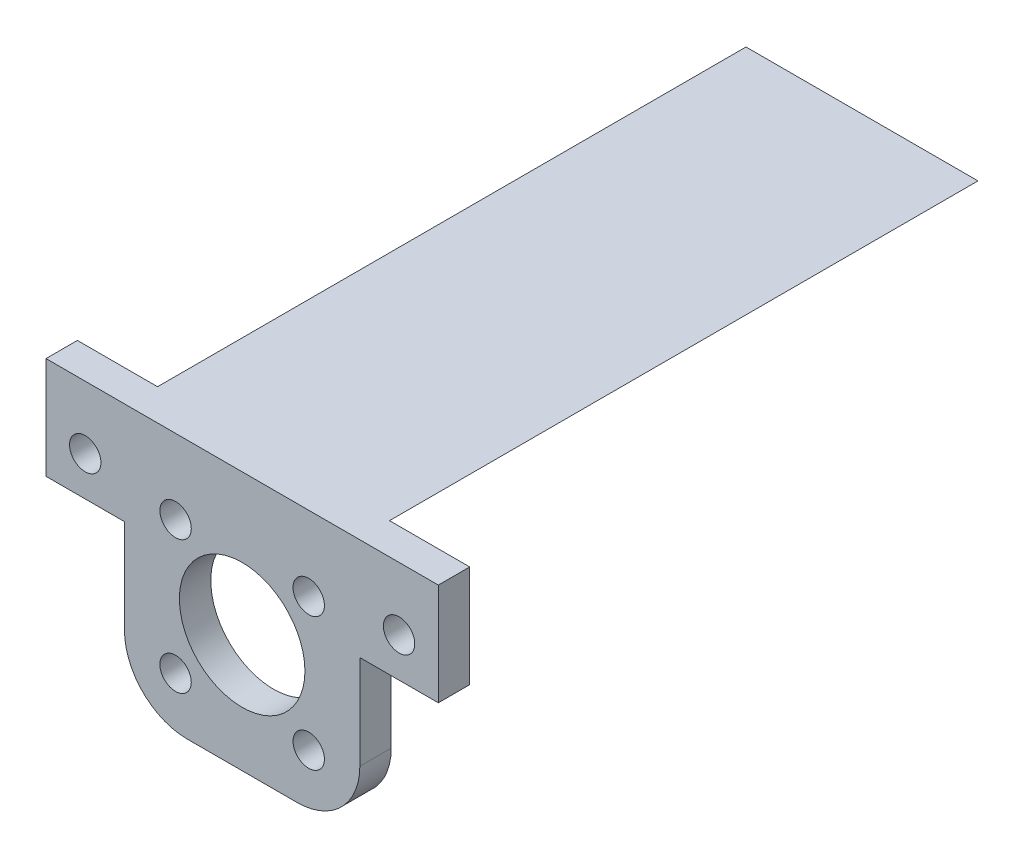
SolidWorks part; units mm, degrees
ref_plane "Alzado" through (0, 0, 0) normal (0, 0, 1) x (1, 0, 0)
ref_plane "Planta" through (0, 0, 0) normal (0, 1, 0) x (1, 0, 0)
ref_plane "Vista lateral" through (0, 0, 0) normal (1, 0, 0) x (0, 0, -1)
sketch "Croquis1" plane through (0, 0, 0) normal (0, 0, 1) x (1, 0, 0)
  line L0 (-25, 33) -> (25, 33)
  line L1 (0, 0) -> (0, 33) construction
  line L2 (-25, 33) -> (-25, 20)
  line L3 (-25, 20) -> (-15, 20)
  line L4 (-15, 20) -> (-15, 8)
  line L5 (-7, 0) -> (7, 0)
  line L6 (25, 33) -> (25, 20)
  line L7 (15, 0) -> (-15, 0) construction
  line L8 (15, 0) -> (15, 30) construction
  line L9 (15, 30) -> (-15, 30) construction
  line L10 (-15, 0) -> (-15, 30) construction
  line L11 (15, 0) -> (-15, 30) construction
  line L12 (15, 30) -> (-15, 0) construction
  line L13 (25, 20) -> (15, 20)
  line L14 (15, 20) -> (15, 8)
  arc A0 (-15, 8) -> (-7, 0) centre (-7, 8) ccw
  circle A1 centre (0, 15) radius 8
  circle A2 centre (-8.4853, 6.5147) radius 2
  circle A3 centre (-8.4853, 23.4853) radius 2
  circle A4 centre (-20, 25) radius 2
  circle A5 centre (8.4853, 6.5147) radius 2
  circle A6 centre (8.4853, 23.4853) radius 2
  circle A7 centre (20, 25) radius 2
  arc A8 (15, 8) -> (7, 0) centre (7, 8) cw
  dimension "D5" = 8
  dimension "D6" = 15
  dimension "D7" = 4
  dimension "D9" = 5
  dimension "D11" = 4
  dimension "D12" = 16
  dimension "D1" = 50
  dimension "D2" = 33
  dimension "D3" = 10
  dimension "D4" = 13
  dimension "D8" = 12
  dimension "D10" = 5
extrude "Saliente-Extruir1" add sketch "Croquis1" along normal blind 4
sketch "Croquis2" plane through (0, 0, 0) normal (0, 0, -1) x (-1, 0, 0)
  line L0 (-15, 30) -> (-15, 33) construction
  line L1 (15, 0) -> (-15, 0) construction
  line L2 (15, 0) -> (15, 30) construction
  line L3 (15, 30) -> (-15, 30) construction
  line L4 (-15, 0) -> (-15, 30) construction
  line L5 (15, 0) -> (-15, 30) construction
  line L6 (15, 30) -> (-15, 0) construction
  line L7 (-25, 33) -> (25, 33) construction
  line L8 (-15, 33) -> (-9.2371, 30) construction
  line L9 (-9.2371, 30) -> (-14.7282, 30)
  line L10 (-14.7282, 30) -> (15, 30) construction
  line L11 (-14.7834, 33) -> (-9.0205, 30)
  line L12 (-14.9538, 33.0887) -> (-9.1909, 30.0887) construction
  line L13 (0, 0) -> (0, 33) construction
  line L14 (15, 30) -> (-15, 30) construction
  line L15 (15, 30) -> (15, 33)
  line L16 (15, 33) -> (-15, 33)
  line L17 (-15, 30) -> (-15, 33)
  line L18 (15, 30) -> (-15, 33) construction
  line L19 (15, 33) -> (-15, 30) construction
  line L20 (14.7834, 33) -> (9.0205, 30)
  line L21 (-14.7834, 33) -> (14.7834, 33)
  line L22 (-9.0205, 30) -> (9.0205, 30)
  point P0 (0, 15)
  point P17 (0, 31.5)
  dimension "D1" = 27.5
  dimension "D2" = 0.1
extrude "Saliente-Extruir2" add sketch "Croquis2" along normal blind 75 contours L11 L22 L20 L16
